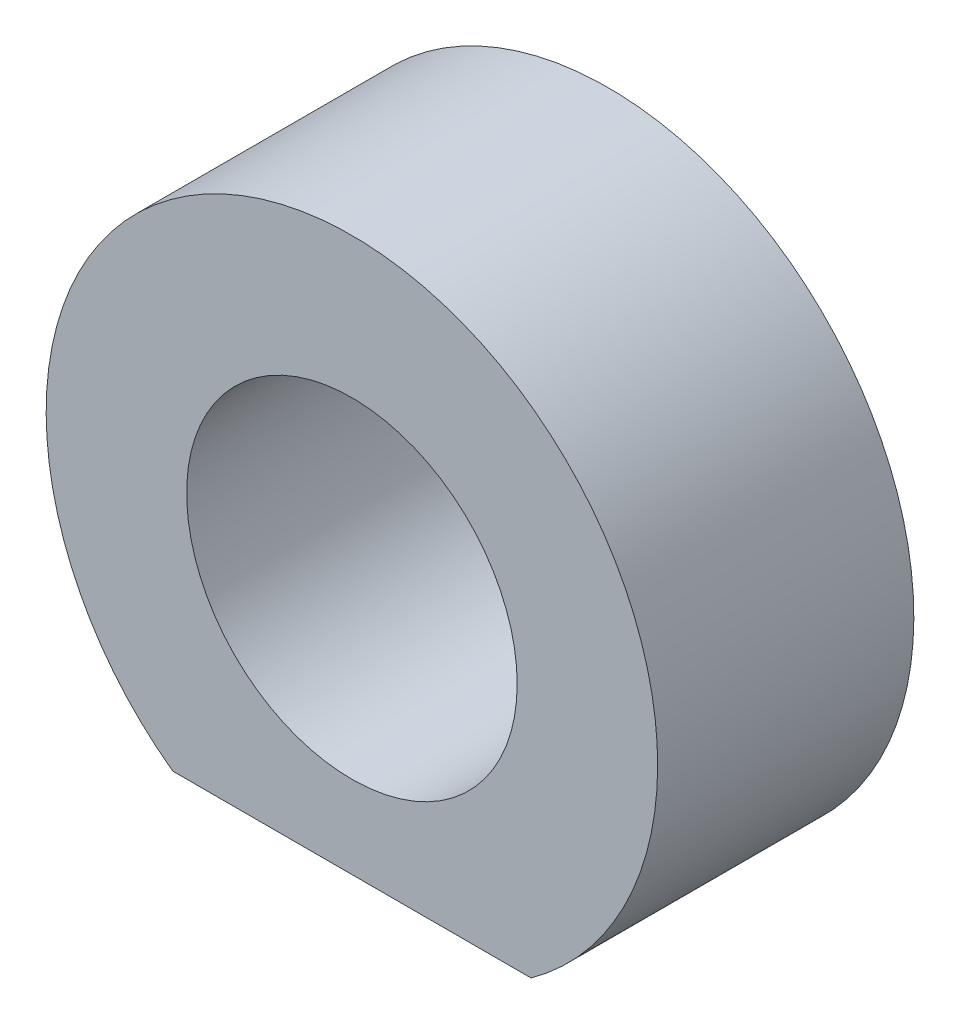
SolidWorks part; units mm, degrees
material "1023 Carbon Steel Sheet (SS)"
ref_plane "Ebene vorne" through (0, 0, 0) normal (0, 0, 1) x (1, 0, 0)
ref_plane "Ebene oben" through (0, 0, 0) normal (0, 1, 0) x (1, 0, 0)
ref_plane "Ebene rechts" through (0, 0, 0) normal (1, 0, 0) x (0, 0, -1)
sketch "Sketch1" plane through (0, 0, 0) normal (0, 0, 1) x (1, 0, 0)
  line L0 (-10.84, -14.9915) -> (10.84, -14.9915)
  line L1 (0, 0) -> (0, -26.6676) construction
  circle A0 centre (0, 0) radius 10
  arc A1 (10.84, -14.9915) -> (-10.84, -14.9915) centre (0, 0) ccw
  dimension "D1" = 20
  dimension "D2" = 37
  dimension "D3" = 21.68
extrude "Boss-Extrude1" add sketch "Sketch1" along normal blind 15.5
hole_wizard "Ø2.0 (2) Diameter Hole1" positions "Sketch2" profile "Sketch3" hole size "Ø2.0" standard "ISO"
sketch "Sketch2" plane through (0, -14.9915, 0) normal (0, -1, 0) x (-1, 0, 0)
  line L0 (10.84, 0) -> (-10.84, 0) construction
  point P0 (0, -7.75)
  dimension "D1" = 7.75
sketch "Sketch3" plane through (0, -14.9915, 7.75) normal (1, 0, 0) x (0, 0, -1)
  line L0 (0, 0) -> (0, 2.6009)
  line L1 (0, 2.6009) -> (1, 2)
  line L2 (1, 2) -> (1, 0.025)
  line L3 (1, 0.025) -> (1.025, 0)
  line L5 (1.025, 0) -> (0, 0)
  line L6 (-1, 0.025) -> (-1.025, 0) construction
  line L10 (0, 2.6009) -> (-1, 2) construction
  line L11 (0, -6.35) -> (0, 107.95) construction
  dimension "Hole Dia." = 2
  dimension "Hole Depth" = 2
  dimension "Near C'Sink Dia." = 2.05
  dimension "Near C'Sink Angle" = 90
  dimension "Drill Angle" = 118
